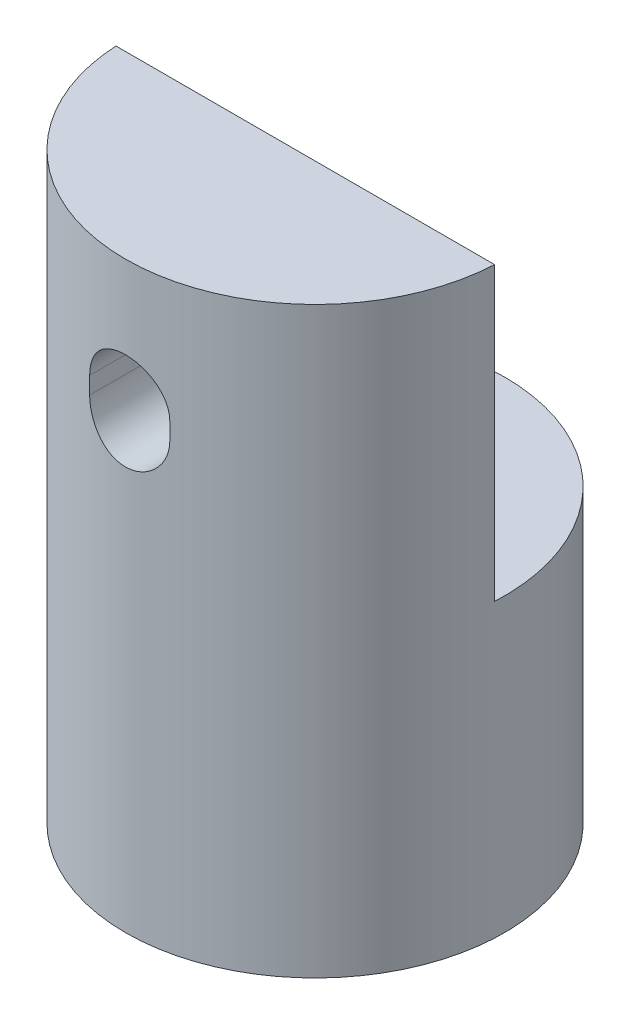
SolidWorks part; units mm, degrees
material "20% infill ABS"
ref_plane "Front" through (0, 0, 0) normal (0, 0, 1) x (1, 0, 0)
ref_plane "Top" through (0, 0, 0) normal (0, 1, 0) x (1, 0, 0)
ref_plane "Right" through (0, 0, 0) normal (1, 0, 0) x (0, 0, -1)
sketch "Sketch1" plane through (0, 0, 0) normal (0, 1, 0) x (1, 0, 0)
  circle A0 centre (0, 0) radius 9.75
  dimension "D1" = 19.5
extrude "Boss-Extrude1" add sketch "Sketch1" along normal blind 30
ref_plane "Plane1" through (9.75, 0, 0) normal (1, 0, 0) x (0, 0, -1)
sketch "Sketch3" plane through (0, 0, 0) normal (0, 0, 1) x (1, 0, 0)
  line L0 (9.75, -10.725) -> (9.75, 10.725) construction
  line L1 (-9.75, 30) -> (9.75, 30)
  line L2 (-9.75, 30) -> (-9.75, 15)
  line L3 (-9.75, 15) -> (9.75, 15)
  line L4 (9.75, 30) -> (9.75, 15)
  dimension "D1" = 15
extrude "Cut-Extrude1" cut sketch "Sketch3" against normal blind 30 and the other way blind 0.5
sketch "Sketch4" plane through (0, 0, 0.5) normal (0, 0, -1) x (-1, 0, 0)
  line L0 (0, 23.6838) -> (0, 22.8038) construction
  line L1 (2.06, 23.6838) -> (2.06, 22.8038)
  line L2 (-2.06, 23.6838) -> (-2.06, 22.8038)
  arc A1 (2.06, 23.6838) -> (-2.06, 23.6838) centre (0, 23.6838) ccw
  arc A2 (-2.06, 22.8038) -> (2.06, 22.8038) centre (0, 22.8038) ccw
  point P2 (0, 23.2438)
  point P8 (2.06, 23.2438)
  point P9 (0, 25.7438)
  point P10 (0, 20.7438)
  dimension "D1" = 4.12
  dimension "D2" = 5
extrude "Cut-Extrude2" cut sketch "Sketch4" against normal blind 30
